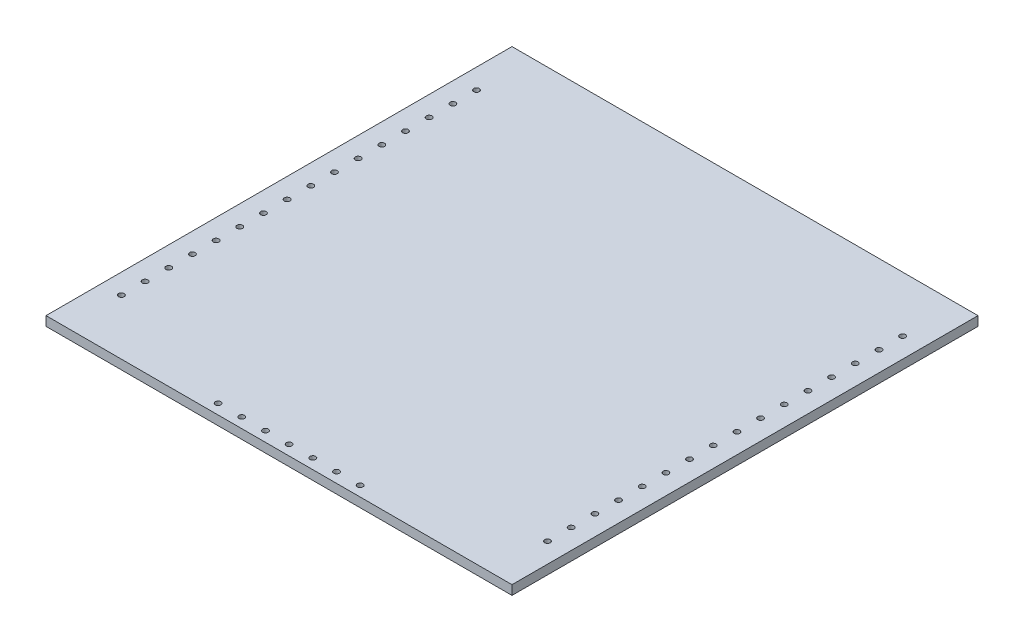
SolidWorks part; units mm, degrees
ref_plane "Спереди" through (0, 0, 0) normal (0, 0, 1) x (1, 0, 0)
ref_plane "Сверху" through (0, 0, 0) normal (0, 1, 0) x (1, 0, 0)
ref_plane "Справа" through (0, 0, 0) normal (1, 0, 0) x (0, 0, -1)
sketch "Эскиз1" plane through (0, 0, 0) normal (0, 1, 0) x (1, 0, 0)
  line L1 (-25, 25) -> (25, 25)
  line L2 (-25, 25) -> (-25, -25)
  line L3 (-25, -25) -> (25, -25)
  line L4 (25, 25) -> (25, -25)
  line L5 (-25, 25) -> (25, -25) construction
  line L6 (-25, -25) -> (25, 25) construction
  point P0 (0, 0)
extrude "Бобышка-Вытянуть1" add sketch "Эскиз1" along normal blind 1
sketch "Эскиз2" plane through (0, 1, 0) normal (0, 1, 0) x (1, 0, 0)
  circle A0 centre (-22.86, -19.05) radius 0.3
  circle A1 centre (-22.86, -16.51) radius 0.3
  circle A2 centre (-22.86, -13.97) radius 0.3
  circle A3 centre (-22.86, -11.43) radius 0.3
  circle A4 centre (-22.86, -8.89) radius 0.3
  circle A5 centre (-22.86, -6.35) radius 0.3
  circle A6 centre (-22.86, -3.81) radius 0.3
  circle A7 centre (-22.86, -1.27) radius 0.3
  circle A8 centre (-22.86, 1.27) radius 0.3
  circle A9 centre (-22.86, 3.81) radius 0.3
  circle A10 centre (-22.86, 6.35) radius 0.3
  circle A11 centre (-22.86, 8.89) radius 0.3
  circle A12 centre (-22.86, 11.43) radius 0.3
  circle A13 centre (-22.86, 13.97) radius 0.3
  circle A14 centre (-22.86, 16.51) radius 0.3
  circle A15 centre (-22.86, 19.05) radius 0.3
  circle A16 centre (22.86, -19.05) radius 0.3
  circle A17 centre (22.86, -16.51) radius 0.3
  circle A18 centre (22.86, -13.97) radius 0.3
  circle A19 centre (22.86, -11.43) radius 0.3
  circle A20 centre (22.86, -8.89) radius 0.3
  circle A21 centre (22.86, -6.35) radius 0.3
  circle A22 centre (22.86, -3.81) radius 0.3
  circle A23 centre (22.86, -1.27) radius 0.3
  circle A24 centre (22.86, 1.27) radius 0.3
  circle A25 centre (22.86, 3.81) radius 0.3
  circle A26 centre (22.86, 6.35) radius 0.3
  circle A27 centre (22.86, 8.89) radius 0.3
  circle A28 centre (22.86, 11.43) radius 0.3
  circle A29 centre (22.86, 13.97) radius 0.3
  circle A30 centre (22.86, 16.51) radius 0.3
  circle A31 centre (22.86, 19.05) radius 0.3
  dimension "D1" = 16
  dimension "D2" = 2
extrude "Вырез-Вытянуть1" cut sketch "Эскиз2" against normal through all
sketch "Эскиз3" plane through (0, 0, 0) normal (0, -1, 0) x (1, 0, 0)
  circle A0 centre (7.62, 23.91) radius 0.3
  circle A1 centre (5.08, 23.91) radius 0.3
  circle A2 centre (2.54, 23.91) radius 0.3
  circle A3 centre (0, 23.91) radius 0.3
  circle A4 centre (-2.54, 23.91) radius 0.3
  circle A5 centre (-5.08, 23.91) radius 0.3
  circle A6 centre (-7.62, 23.91) radius 0.3
  dimension "D1" = 7
extrude "Вырез-Вытянуть2" cut sketch "Эскиз3" against normal through all
